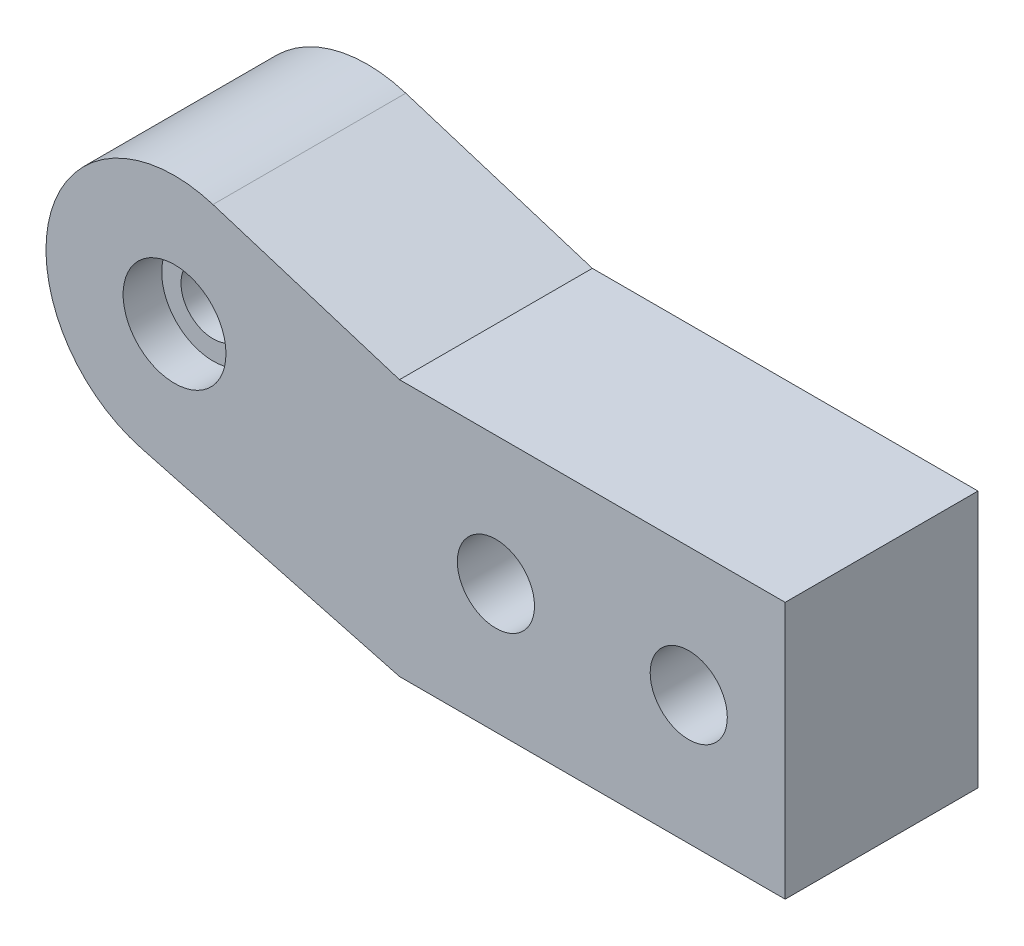
SolidWorks part; units mm, degrees
ref_plane "前视基准面" through (0, 0, 0) normal (0, 0, 1) x (1, 0, 0)
ref_plane "上视基准面" through (0, 0, 0) normal (0, 1, 0) x (1, 0, 0)
ref_plane "右视基准面" through (0, 0, 0) normal (1, 0, 0) x (0, 0, -1)
other "Configuration Table"
sketch "草图1" plane through (0, 0, 0) normal (0, 0, 1) x (1, 0, 0)
  line L0 (-30, 0) -> (0, 0)
  line L1 (0, 0) -> (0, -20)
  line L2 (0, -20) -> (-30, -20)
  line L3 (0, -10) -> (-50000, -10) construction
  line L5 (-47.5, -1.2569) -> (-47.5, -50001.2569) construction
  line L6 (-30, 0) -> (-44.5124, 4.5433)
  line L7 (-30, -20) -> (-50.0694, -14.6643)
  line L8 (-30, 0) -> (-30, -20) construction
  circle A1 centre (-22.5, -10) radius 3
  circle A2 centre (-7.5, -10) radius 3
  arc A3 (-44.5124, 4.5433) -> (-50.0694, -14.6643) centre (-47.5, -5) ccw
  point P17 (0, -10)
  dimension "D1" = 6
  dimension "D2" = 6
  dimension "D7" = 20
  dimension "D3" = 15
  dimension "D4" = 7.5
  dimension "D5" = 30
  dimension "D6" = 20
  dimension "D8" = 25
  dimension "D9" = 5
extrude "凸台-拉伸1" add sketch "草图1" along normal blind 15
sketch "草图4" plane through (0, 0, 0) normal (0, 0, -1) x (-1, 0, 0)
  circle A0 centre (7.5, -10) radius 5
  circle A1 centre (22.5, -10) radius 5
  dimension "D1" = 10
  dimension "D2" = 10
extrude "切除-拉伸3" cut sketch "草图4" against normal blind 6
sketch "草图8" plane through (0, 0, 15) normal (0, 0, 1) x (1, 0, 0)
  circle A0 centre (-47.5, -5) radius 4
  dimension "D1" = 8
extrude "切除-拉伸4" cut sketch "草图8" against normal blind 3
sketch "草图10" plane through (0, 0, 12) normal (0, 0, 1) x (1, 0, 0)
  circle A0 centre (-47.5, -5) radius 2.5
  dimension "D1" = 5
extrude "切除-拉伸5" cut sketch "草图10" against normal blind 10
